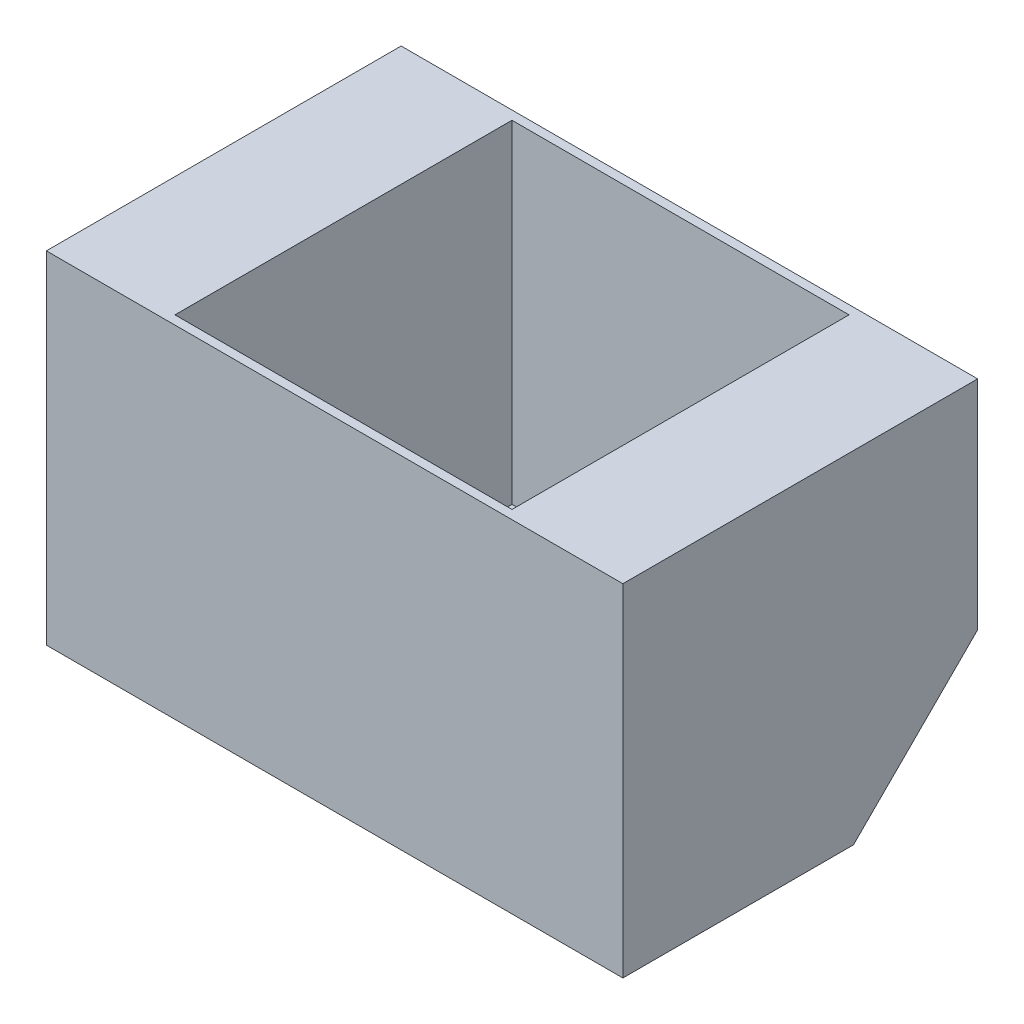
SolidWorks part; units mm, degrees
ref_plane "Front Plane" through (0, 0, 0) normal (0, 0, 1) x (1, 0, 0)
ref_plane "Top Plane" through (0, 0, 0) normal (0, 1, 0) x (1, 0, 0)
ref_plane "Right Plane" through (0, 0, 0) normal (1, 0, 0) x (0, 0, -1)
sketch "Sketch1" plane through (0, 0, 0) normal (0, 1, 0) x (1, 0, 0)
  line L1 (-40, 40) -> (40, 40)
  line L2 (-40, 40) -> (-40, -40)
  line L3 (-40, -40) -> (40, -40)
  line L4 (40, 40) -> (40, -40)
  line L5 (-40, 40) -> (40, -40) construction
  line L6 (-40, -40) -> (40, 40) construction
  circle A0 centre (0, 0) radius 18.4
  point P0 (0, 0)
  dimension "D3" = 36.8
  dimension "D1" = 80
  dimension "D2" = 80
extrude "Boss-Extrude1" add sketch "Sketch1" along normal blind 2
sketch "Sketch2" plane through (0, 2, 0) normal (0, 1, 0) x (1, 0, 0)
  line L1 (40, -40) -> (44, -40)
  line L2 (40, -40) -> (40, -21.5)
  line L3 (40, -21.5) -> (44, -21.5)
  line L4 (44, -40) -> (44, -21.5)
  dimension "D1" = 18.5
  dimension "D2" = 4
extrude "Boss-Extrude2" add sketch "Sketch2" against normal blind 15.25
sketch "Sketch3" plane through (44, 0, 0) normal (1, 0, 0) x (0, 0, -1)
  line L1 (-40, -13.25) -> (-21.5, -13.25) construction
  line L4 (-40, -13.25) -> (-40, 2) construction
  circle A0 centre (-30.75, -8.125) radius 2.2
  dimension "D1" = 4.4
  dimension "D2" = 5.125
  dimension "D3" = 9.25
extrude "Cut-Extrude1" cut sketch "Sketch3" against normal through all
ref_plane "Plane1" through (0, 0, 0) normal (1, 0, 0) x (0, 0, -1)
mirror "Mirror1" about plane through (0, 0, 0) normal (1, 0, 0) of "Cut-Extrude1", "Boss-Extrude2"
ref_plane "Plane2" through (0, 0, 0) normal (0, 0, -1) x (-1, 0, 0)
mirror "Mirror2" about plane through (0, 0, 0) normal (0, 0, -1) of "Mirror1", "Cut-Extrude1", "Boss-Extrude2"
sketch "Sketch4" plane through (0, 2, 0) normal (0, 1, 0) x (1, 0, 0)
  line L1 (44, 40) -> (-44, 40) construction
  line L2 (-40, 21.5) -> (-40, -21.5) construction
  circle A1 centre (-24, 24) radius 2.2
  circle A4 centre (24, 24) radius 2.2
  dimension "D1" = 16
  dimension "D2" = 16
  dimension "D3" = 2
extrude "Cut-Extrude2" cut sketch "Sketch4" against normal through all
mirror "Mirror3" about plane through (0, 0, 0) normal (0, 0, -1) of "Cut-Extrude2"
sketch "Sketch5" plane through (0, 0, 40) normal (0, 0, 1) x (1, 0, 0)
  line L1 (-40, -13.25) -> (-44, -13.25)
  line L2 (-40, -13.25) -> (-40, 2)
  line L3 (-40, 2) -> (-44, 2)
  line L4 (-44, -13.25) -> (-44, 2)
  line L5 (40, -13.25) -> (44, -13.25)
  line L6 (40, -13.25) -> (40, 2)
  line L7 (40, 2) -> (44, 2)
  line L8 (44, -13.25) -> (44, 2)
extrude "Cut-Extrude3" cut sketch "Sketch5" against normal through all
sketch "Sketch6" plane through (0, 2, 0) normal (0, 1, 0) x (1, 0, 0)
  line L1 (-40, 40) -> (40, 40)
  line L2 (-40, 40) -> (-40, -40)
  line L3 (-40, -40) -> (40, -40)
  line L4 (40, 40) -> (40, -40)
  line L5 (38, 38) -> (-38, 38)
  line L6 (38, 38) -> (38, -38)
  line L7 (38, -38) -> (-38, -38)
  line L8 (-38, 38) -> (-38, -38)
  line L9 (38, 38) -> (-38, -38) construction
  line L10 (38, -38) -> (-38, 38) construction
  point P6 (0, 0)
  dimension "D1" = 76
  dimension "D2" = 76
extrude "Boss-Extrude3" add sketch "Sketch6" along normal blind 75
sketch "Sketch7" plane through (0, 0, 40) normal (0, 0, 1) x (1, 0, 0)
  line L0 (40, 0) -> (65, 0)
  line L2 (-40, 0) -> (-65, 0)
  line L4 (-65, 0) -> (-40, 0)
  line L5 (-65, 0) -> (-65, 77)
  line L6 (-65, 77) -> (-40, 77)
  line L7 (-40, 0) -> (-40, 77)
  line L8 (65, 0) -> (40, 0)
  line L9 (65, 0) -> (65, 77)
  line L10 (65, 77) -> (40, 77)
  line L11 (40, 0) -> (40, 77)
  line M4 (40, 0) -> (40, 77)
  line M6 (-40, 77) -> (-40, 0)
  dimension "D1" = 25
  dimension "D2" = 25
extrude "Boss-Extrude4" add sketch "Sketch7" against normal blind 80 contours L6 L5 L2 M6 | L9 L10 L0 M4
sketch "Sketch9" plane through (65, 0, 0) normal (1, 0, 0) x (0, 0, -1)
  line L7 (26, 28) -> (12, 14)
  line L8 (40, 0) -> (12, 0)
  line L9 (40, 0) -> (40, 28)
  line L10 (40, 28) -> (12, 28)
  line L11 (12, 0) -> (12, 28)
  line L12 (12, 14) -> (12, 0)
  line L13 (40, 28) -> (12, 0)
  line M9 (-40, 0) -> (40, 0)
  line M10 (40, 0) -> (40, 77)
  dimension "D1" = 28
  dimension "D2" = 28
extrude "Cut-Extrude5" cut sketch "Sketch9" against normal blind 21 contours L13 M10 M9
mirror "Mirror4" about plane through (0, 0, 0) normal (1, 0, 0) of "Cut-Extrude5"
